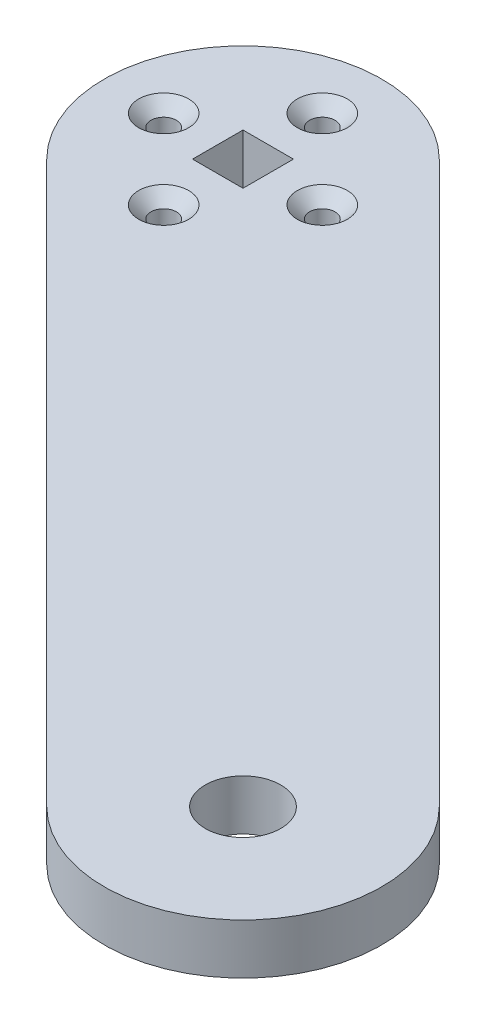
SolidWorks part; units mm, degrees
other "Markup1"
sketch "Sketch6" plane through (50.3553, 0, 50.3553) normal (0.291, 0.9567, 0.0091) x (0.9567, -0.291, -0.0015)
material "5052-H32"
ref_plane "Front Plane" through (0, 0, 0) normal (0, 0, 1) x (1, 0, 0)
ref_plane "Top Plane" through (0, 0, 0) normal (0, 1, 0) x (1, 0, 0)
ref_plane "Right Plane" through (0, 0, 0) normal (1, 0, 0) x (0, 0, -1)
sketch "Sketch2" plane through (0, 0, 0) normal (0, 1, 0) x (1, 0, 0)
  line L0 (0, 0) -> (70.7107, -70.7107) construction
  line L1 (-3.18, 3.18) -> (3.18, 3.18)
  line L2 (-3.18, 3.18) -> (-3.18, -3.18)
  line L3 (-3.18, -3.18) -> (3.18, -3.18)
  line L4 (3.18, 3.18) -> (3.18, -3.18)
  line L5 (0, 0) -> (70.7107, 0) construction
  line L6 (-12.3744, -12.3744) -> (12.3744, 12.3744) construction
  line L7 (12.3744, 12.3744) -> (83.085, -58.3363)
  line L8 (-12.3744, -12.3744) -> (58.3363, -83.085)
  circle A0 centre (70.7107, -70.7107) radius 4.7625
  arc A1 (12.3744, 12.3744) -> (-12.3744, -12.3744) centre (0, 0) ccw
  arc A2 (83.085, -58.3363) -> (58.3363, -83.085) centre (70.7107, -70.7107) cw
  circle A3 centre (0, 10) radius 1.5 construction
  circle A4 centre (-10, 0) radius 1.5 construction
  circle A5 centre (0, 0) radius 10 construction
  circle A8 centre (70.7107, -70.7107) radius 37 construction
  circle A9 centre (10, 0) radius 1.5 construction
  circle A10 centre (0, -10) radius 1.5 construction
  point P4 (0, 3.18)
  point P6 (3.18, 0)
  point P13 (0, 0)
  point P64 (-35.6107, -7.3081)
  point P66 (-35.4789, -10.4526)
  dimension "D4" = 9.525
  dimension "D5" = 17.5
  dimension "D6" = 17.5
  dimension "D7" = 3
  dimension "D8" = 20
  dimension "D9" = 74
  dimension "D1" = 6.36
  dimension "D2" = 45
  dimension "D3" = 100
extrude "Boss-Extrude1" add sketch "Sketch2" against normal blind 6.35 contours A1 L8 A2 L7
hole_wizard "CSK for M3 Flat Head Machine Screw1" positions "3DSketch1" profile "Sketch3" countersink size "M3" standard "ANSI Metric" end condition up to next
sketch3d "3DSketch1"
  point P0 (0, 0, -10)
  point P2 (-10, 0, 0)
  point P4 (10, 0, 0)
  point P13 (0, 0, 10)
sketch "Sketch3" plane through (0, 0, -10) normal (1, 0, 0) x (0, 0, 1)
  line L0 (0, 0) -> (0, 6.35)
  line L1 (0, 6.35) -> (1.6, 6.35)
  line L2 (1.6, 6.35) -> (1.6, 1.55)
  line L3 (1.6, 1.55) -> (3.15, 0)
  line L5 (3.15, 0) -> (0, 0)
  line L6 (-1.6, 1.55) -> (-3.15, 0) construction
  line L11 (0, -6.35) -> (0, 107.95) construction
  dimension "Thru Hole Dia." = 3.2
  dimension "Thru Hole Depth" = 6.35
  dimension "Near C'Sink Dia." = 6.3
  dimension "Near C'Sink Angle" = 90
